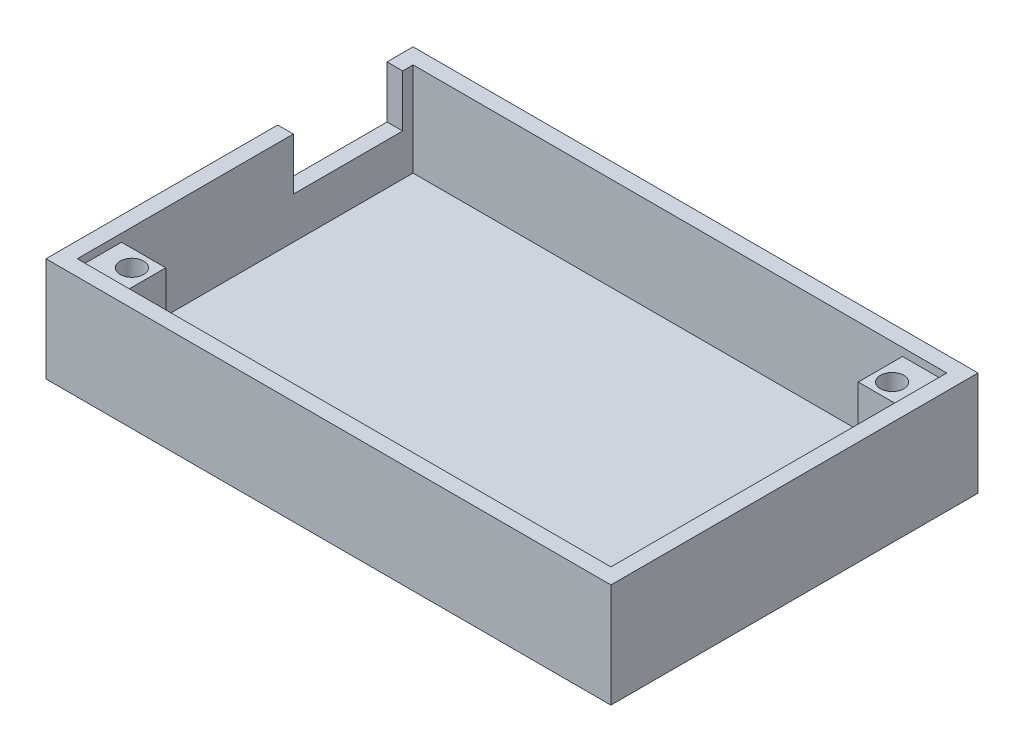
SolidWorks part; units mm, degrees
ref_plane "Front Plane" through (0, 0, 0) normal (0, 0, 1) x (1, 0, 0)
ref_plane "Top Plane" through (0, 0, 0) normal (0, 1, 0) x (1, 0, 0)
ref_plane "Right Plane" through (0, 0, 0) normal (1, 0, 0) x (0, 0, -1)
sketch "Sketch1" plane through (0, 0, 0) normal (0, 1, 0) x (1, 0, 0)
  line L1 (54.25, -35.25) -> (-54.25, -35.25)
  line L2 (54.25, -35.25) -> (54.25, 35.25)
  line L3 (54.25, 35.25) -> (-54.25, 35.25)
  line L4 (-54.25, -35.25) -> (-54.25, 35.25)
  line L5 (54.25, -35.25) -> (-54.25, 35.25) construction
  line L6 (54.25, 35.25) -> (-54.25, -35.25) construction
  point P0 (0, 0)
  dimension "D1" = 108.5
  dimension "D2" = 70.5
extrude "Boss-Extrude1" add sketch "Sketch1" along normal blind 20
sketch "Sketch2" plane through (0, 20, 0) normal (0, 1, 0) x (1, 0, 0)
  line L1 (51.25, -32.25) -> (-51.25, -32.25)
  line L2 (51.25, -32.25) -> (51.25, 32.25)
  line L3 (51.25, 32.25) -> (-51.25, 32.25)
  line L4 (-51.25, -32.25) -> (-51.25, 32.25)
  line L5 (51.25, -32.25) -> (-51.25, 32.25) construction
  line L6 (51.25, 32.25) -> (-51.25, -32.25) construction
  point P0 (0, 0)
  dimension "D1" = 102.5
  dimension "D2" = 64.5
extrude "Cut-Extrude1" cut sketch "Sketch2" against normal blind 18
sketch "Sketch3" plane through (0, 2, 0) normal (0, 1, 0) x (1, 0, 0)
  line L1 (-51.25, -32.25) -> (-42.75, -32.25)
  line L2 (-51.25, -32.25) -> (-51.25, -23.75)
  line L3 (-51.25, -23.75) -> (-42.75, -23.75)
  line L4 (-42.75, -32.25) -> (-42.75, -23.75)
  dimension "D1" = 8.5
extrude "Boss-Extrude2" add sketch "Sketch3" along normal blind 16.5
sketch "Sketch4" plane through (0, 18.5, 0) normal (0, 1, 0) x (1, 0, 0)
  line L0 (-51.25, -23.75) -> (-51.25, -32.25) construction
  line L1 (-51.25, -32.25) -> (-42.75, -32.25) construction
  circle A0 centre (-46, -27) radius 2.25
  dimension "D1" = 4.5
  dimension "D2" = 3
  dimension "D3" = 3
extrude "Cut-Extrude2" cut sketch "Sketch4" against normal blind 15
sketch "Sketch7" plane through (-51.25, 0, 0) normal (1, 0, 0) x (0, 0, -1)
  line L0 (32.25, 20) -> (-32.25, 20) construction
  line L1 (9.25, 20) -> (30.25, 20)
  line L2 (9.25, 20) -> (9.25, 10)
  line L3 (9.25, 10) -> (30.25, 10)
  line L4 (30.25, 20) -> (30.25, 10)
  line L5 (32.25, 2) -> (32.25, 20) construction
  dimension "D1" = 21
  dimension "D2" = 2
  dimension "D3" = 10
extrude "Cut-Extrude5" cut sketch "Sketch7" against normal blind 8
sketch "Sketch8" plane through (0, 2, 0) normal (0, 1, 0) x (1, 0, 0)
  line L2 (51.25, 32.25) -> (42.75, 32.25)
  line L3 (51.25, 32.25) -> (51.25, 23.75)
  line L4 (51.25, 23.75) -> (42.75, 23.75)
  line L5 (42.75, 32.25) -> (42.75, 23.75)
  dimension "D1" = 8.5
extrude "Boss-Extrude3" add sketch "Sketch8" along normal blind 16.5 contours L5 L4 L3 L2
sketch "Sketch9" plane through (0, 18.5, 0) normal (0, 1, 0) x (1, 0, 0)
  line L1 (51.25, 32.25) -> (51.25, 23.75) construction
  line L2 (51.25, 32.25) -> (42.75, 32.25) construction
  circle A0 centre (46, 27) radius 2.25
  point P4 (0, 0)
  dimension "D1" = 4.5
  dimension "D2" = 3
  dimension "D3" = 3
extrude "Cut-Extrude6" cut sketch "Sketch9" against normal blind 15 and the other way blind 13
equation "\"16.5.00mm\"=15"
